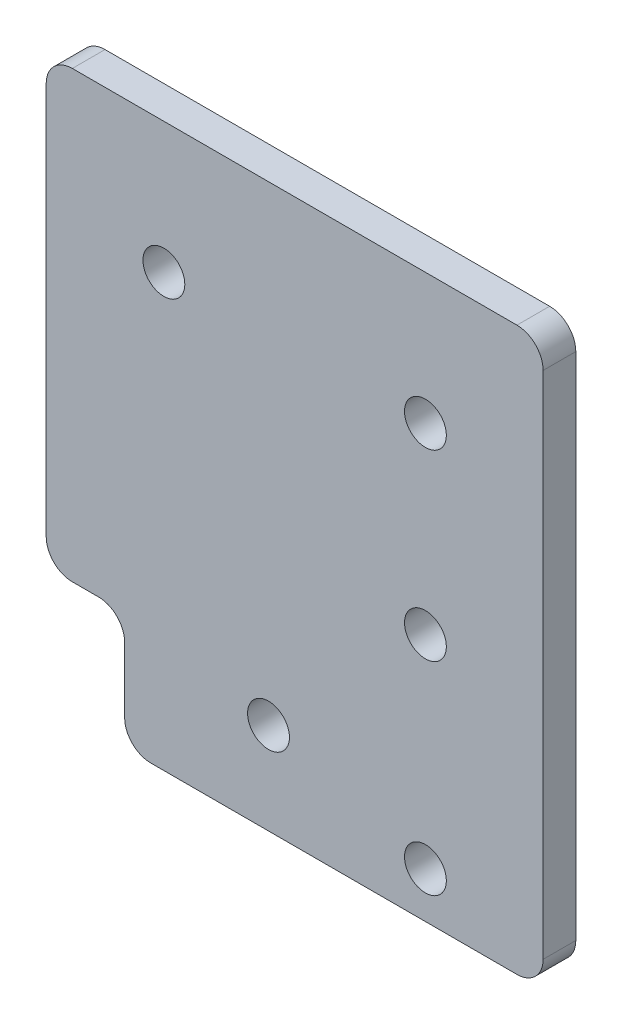
SolidWorks part; units mm, degrees
ref_plane "前视基准面" through (0, 0, 0) normal (0, 0, 1) x (1, 0, 0)
ref_plane "上视基准面" through (0, 0, 0) normal (0, 1, 0) x (1, 0, 0)
ref_plane "右视基准面" through (0, 0, 0) normal (1, 0, 0) x (0, 0, -1)
sketch "草图1" plane through (0, 0, 0) normal (0, 0, 1) x (1, 0, 0)
  line L1 (-19, 17) -> (19, 17)
  line L2 (-19, 17) -> (-19, -17)
  line L3 (-13, -26) -> (19, -26)
  line L4 (19, 17) -> (19, -26)
  line L7 (-19, -17) -> (-13, -17)
  line L8 (-13, -26) -> (-13, -17)
  circle A0 centre (10, 7) radius 1.6
  circle A1 centre (-10, 7) radius 1.6
  circle A2 centre (10, -22.5) radius 1.6
  circle A4 centre (10, -7) radius 1.6
  circle A5 centre (-2, -19) radius 1.6
  point P2 (0, 0)
  point P4 (0, 17)
  point P6 (-19, 0)
  dimension "D3" = 3.2
  dimension "D2" = 43
  dimension "D4" = 20
  dimension "D5" = 10
  dimension "D6" = 9
  dimension "D7" = 12.5
  dimension "D9" = 32
  dimension "D10" = 34
  dimension "D11" = 38
  dimension "D12" = 12
  dimension "D13" = 24
  dimension "D14" = 12
extrude "凸台-拉伸1" add sketch "草图1" along normal blind 2.5
fillet "圆角2" radius 2 6 edges at (-19, 17, 1.25) (19, 17, 1.25) (19, -26, 1.25) (-13, -26, 1.25) (-19, -17, 1.25) (-13, -17, 1.25)
